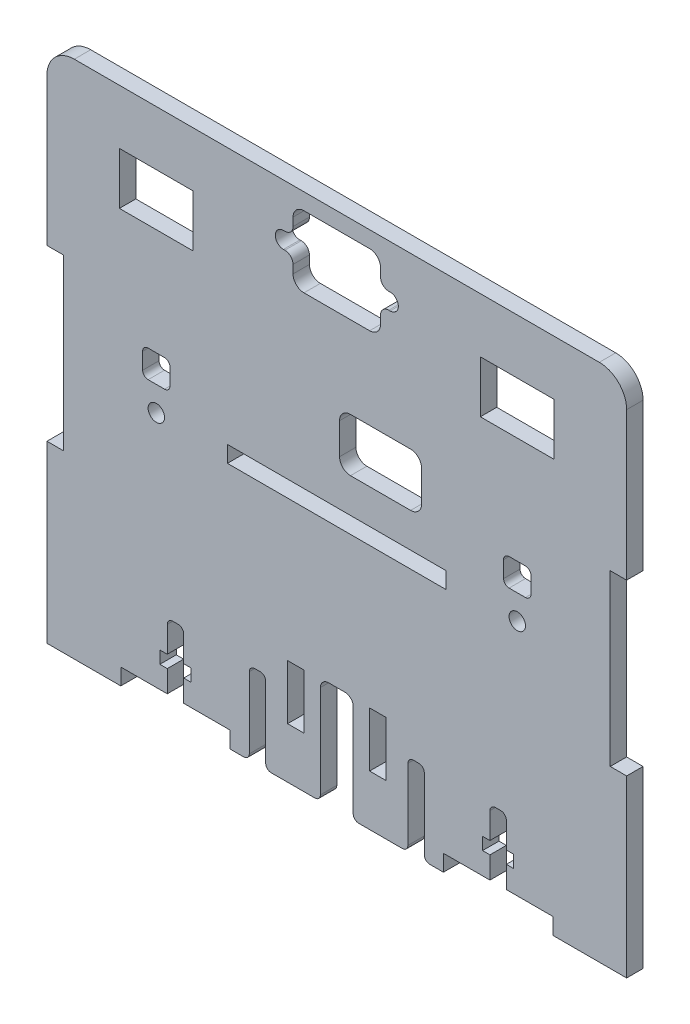
SolidWorks part; units mm, degrees
other "Marcação1"
sketch "Esboço7" plane through (-68, 31.5, 3) normal (-0.6758, 0.2828, 0.6807) x (0.7271, 0.1043, 0.6785)
sketch "Esboço8" plane through (-68, 31.5, 3) normal (-0.6758, 0.2828, 0.6807) x (0.7271, 0.1043, 0.6785)
sketch "Esboço9" plane through (-60.5, 31.5, 3) normal (-0.6758, 0.2828, 0.6807) x (0.7271, 0.1043, 0.6785)
sketch "Esboço12" plane through (-60.5, 31.5, 3) normal (-0.6758, 0.2828, 0.6807) x (0.7271, 0.1043, 0.6785)
sketch "Esboço14" plane through (-60.5, 31.5, 3) normal (-0.6758, 0.2828, 0.6807) x (0.7271, 0.1043, 0.6785)
sketch "Esboço15" plane through (-60.5, 36.25, 3) normal (-0.6758, 0.2828, 0.6807) x (0.7271, 0.1043, 0.6785)
sketch "Esboço18" plane through (-60.5, 33.25, 3) normal (-0.6758, 0.2828, 0.6807) x (0.7271, 0.1043, 0.6785)
sketch "Esboço20" plane through (-60.5, 29.8, 3) normal (-0.6758, 0.2828, 0.6807) x (0.7271, 0.1043, 0.6785)
sketch "Esboço22" plane through (-60.5, 29.8, 3) normal (-0.6758, 0.2828, 0.6807) x (0.7271, 0.1043, 0.6785)
material "Acrylic (Medium-high impact)"
ref_plane "Plano frontal" through (0, 0, 0) normal (0, 0, 1) x (1, 0, 0)
ref_plane "Plano superior" through (0, 0, 0) normal (0, 1, 0) x (1, 0, 0)
ref_plane "Plano direito" through (0, 0, 0) normal (1, 0, 0) x (0, 0, -1)
sketch "Esboço1" plane through (0, 0, 0) normal (0, 0, 1) x (1, 0, 0)
  line L1 (-50, -47.5) -> (50, -47.5)
  line L2 (-50, -47.5) -> (-50, 47.5)
  line L3 (-50, 47.5) -> (50, 47.5)
  line L4 (50, -47.5) -> (50, 47.5)
  line L5 (-50, -47.5) -> (50, 47.5) construction
  line L6 (-50, 47.5) -> (50, -47.5) construction
  point P0 (0, 0)
  dimension "D1" = 100
  dimension "D2" = 95
extrude "Ressalto-extrusão1" add sketch "Esboço1" along normal mid plane 3
sketch "Esboço3" plane through (0, 0, 1.5) normal (0, 0, 1) x (1, 0, 0)
  line L20 (50, 47.5) -> (-50, 47.5) construction
  line L21 (-53, 47.5) -> (-50, 47.5)
  line L22 (-53, 47.5) -> (-53, 15.5)
  line L23 (-53, 15.5) -> (-50, 15.5)
  line L24 (-50, 47.5) -> (-50, 15.5)
  line L25 (-50, 47.5) -> (-50, -47.5) construction
  line L26 (0, -1.65) -> (0, 1.65) construction
  line L27 (-50, -47.5) -> (-53, -47.5)
  line L28 (-50, -47.5) -> (-50, -15.5)
  line L29 (-50, -15.5) -> (-53, -15.5)
  line L30 (-53, -47.5) -> (-53, -15.5)
  line L31 (53, -47.5) -> (53, -15.5)
  line L32 (50, -15.5) -> (53, -15.5)
  line L33 (50, -47.5) -> (50, -15.5)
  line L34 (50, -47.5) -> (53, -47.5)
  line L35 (50, 47.5) -> (50, 15.5)
  line L36 (53, 15.5) -> (50, 15.5)
  line L37 (53, 47.5) -> (53, 15.5)
  line L38 (53, 47.5) -> (50, 47.5)
  dimension "D1" = 3
  dimension "D4" = 31
extrude "Ressalto-extrusão2" add sketch "Esboço3" against normal through all
sketch "Esboço2" plane through (0, 0, 1.5) normal (0, 0, 1) x (1, 0, 0)
  line L21 (-20, 0.5) -> (20, 0.5)
  line L22 (-20, 0.5) -> (-20, -2.5)
  line L23 (-20, -2.5) -> (20, -2.5)
  line L24 (20, 0.5) -> (20, -2.5)
  line L25 (-20, 0.5) -> (20, -2.5) construction
  line L26 (-20, -2.5) -> (20, 0.5) construction
  line L27 (0, -1.65) -> (0, 1.65) construction
  line L28 (-53, -47.5) -> (53, -47.5) construction
  circle A2 centre (-33, -1) radius 1.5
  circle A4 centre (33, -1) radius 1.5
  point P14 (0, -1)
  dimension "D4" = 13
  dimension "D8" = 3
  dimension "D3" = 45
  dimension "D6" = 3
  dimension "D13" = 40
extrude "Corte-extrusão1" cut sketch "Esboço2" against normal through all
sketch "Sketch4" plane through (0, 0, 1.5) normal (0, 0, 1) x (1, 0, 0)
  line L0 (-33, -2.5) -> (-33, 0.5) construction
  line L4 (0, -1.65) -> (0, 1.65) construction
  line L5 (-34.5, 8.5) -> (-31.5, 8.5)
  line L6 (-35.5, 7.5) -> (-35.5, 4.5)
  line L7 (-34.5, 3.5) -> (-31.5, 3.5)
  line L8 (-30.5, 7.5) -> (-30.5, 4.5)
  line L9 (30.5, 7.5) -> (30.5, 4.5)
  line L10 (34.5, 3.5) -> (31.5, 3.5)
  line L11 (35.5, 7.5) -> (35.5, 4.5)
  line L12 (34.5, 8.5) -> (31.5, 8.5)
  circle A1 centre (-33, -1) radius 1.5 construction
  arc A2 (-31.5, 8.5) -> (-30.5, 7.5) centre (-31.5, 7.5) cw
  arc A3 (-34.5, 8.5) -> (-35.5, 7.5) centre (-34.5, 7.5) ccw
  arc A4 (-35.5, 4.5) -> (-34.5, 3.5) centre (-34.5, 4.5) ccw
  arc A5 (-31.5, 3.5) -> (-30.5, 4.5) centre (-31.5, 4.5) ccw
  arc A6 (31.5, 3.5) -> (30.5, 4.5) centre (31.5, 4.5) cw
  arc A7 (35.5, 4.5) -> (34.5, 3.5) centre (34.5, 4.5) cw
  arc A8 (34.5, 8.5) -> (35.5, 7.5) centre (34.5, 7.5) cw
  arc A9 (31.5, 8.5) -> (30.5, 7.5) centre (31.5, 7.5) ccw
  point P10 (-33, 3.5)
  point P15 (-35.5, 8.5)
  point P18 (-35.5, 3.5)
  point P35 (35.5, 3.5)
  point P36 (35.5, 8.5)
  dimension "D1" = 5
  dimension "D2" = 5
  dimension "D4" = 1
  dimension "D3" = 3
extrude "Cut-Extrude3" cut sketch "Sketch4" against normal through all both and the other way through all
sketch "Sketch6" plane through (0, 0, 0) normal (0, 0, 1) x (1, 0, 0)
  line L0 (0, 44.5) -> (0, 31.5) construction
  line L2 (-6, 44.5) -> (6, 44.5)
  line L3 (-8, 42.5) -> (-8, 41)
  line L4 (-6, 31.5) -> (6, 31.5)
  line L5 (8, 42.5) -> (8, 41)
  line L6 (53, 47.5) -> (-53, 47.5) construction
  line L7 (-9.75, 39.5) -> (-9.5, 39.5)
  line L9 (-9.75, 36.5) -> (-9.5, 36.5)
  line L11 (-8, 35) -> (-8, 33.5)
  line L12 (9.75, 39.5) -> (9.5, 39.5)
  line L13 (9.75, 36.5) -> (9.5, 36.5)
  line L14 (8, 35) -> (8, 33.5)
  arc A0 (-9.75, 39.5) -> (-9.75, 36.5) centre (-9.75, 38) ccw
  arc A1 (9.75, 36.5) -> (9.75, 39.5) centre (9.75, 38) ccw
  arc A2 (-9.5, 36.5) -> (-8, 35) centre (-9.5, 35) cw
  arc A3 (-9.5, 39.5) -> (-8, 41) centre (-9.5, 41) ccw
  arc A4 (6, 31.5) -> (8, 33.5) centre (6, 33.5) ccw
  arc A5 (-8, 33.5) -> (-6, 31.5) centre (-6, 33.5) ccw
  arc A6 (6, 44.5) -> (8, 42.5) centre (6, 42.5) cw
  arc A7 (-6, 44.5) -> (-8, 42.5) centre (-6, 42.5) ccw
  arc A8 (9.5, 36.5) -> (8, 35) centre (9.5, 35) ccw
  arc A9 (9.5, 39.5) -> (8, 41) centre (9.5, 41) cw
  point P7 (0, 31.5)
  point P19 (-8, 36.5)
  point P26 (-8, 31.5)
  point P29 (8, 44.5)
  point P32 (-8, 44.5)
  point P37 (8, 36.5)
  dimension "D4" = 19.5
  dimension "D7" = 2
  dimension "D8" = 5
  dimension "D5" = 3
  dimension "D6" = 1.5
  dimension "D9" = 1.5
  dimension "D1" = 16
  dimension "D2" = 3
  dimension "D3" = 13
extrude "Cut-Extrude5" cut sketch "Sketch6" against normal through all both and the other way through all
sketch "Sketch7" plane through (0, 0, 0) normal (0, 0, 1) x (1, 0, 0)
  line L1 (-39.75, 37.5) -> (-26.25, 37.5)
  line L2 (-39.75, 37.5) -> (-39.75, 28)
  line L3 (-39.75, 28) -> (-26.25, 28)
  line L4 (-26.25, 37.5) -> (-26.25, 28)
  line L5 (0, -1.65) -> (0, 1.65) construction
  line L6 (-31.5, 8.5) -> (-34.5, 8.5) construction
  line L7 (-33, 3.5) -> (-33, 8.5) construction
  line L8 (-34.5, 3.5) -> (-31.5, 3.5) construction
  line L9 (26.25, 37.5) -> (26.25, 28)
  line L10 (39.75, 28) -> (26.25, 28)
  line L11 (39.75, 37.5) -> (39.75, 28)
  line L12 (39.75, 37.5) -> (26.25, 37.5)
  line L13 (53, 47.5) -> (-53, 47.5) construction
  point P13 (-33, 28)
  dimension "D1" = 13.5
  dimension "D2" = 9.5
  dimension "D3" = 10
extrude "Cut-Extrude6" cut sketch "Sketch7" against normal through all both and the other way through all
sketch "Sketch8" plane through (0, 0, 0) normal (0, 0, 1) x (1, 0, 0)
  line L0 (0, -1.65) -> (0, 1.65) construction
  line L1 (-9, -28.23) -> (-6, -28.23)
  line L2 (-9, -28.23) -> (-9, -38.23)
  line L3 (-9, -38.23) -> (-6, -38.23)
  line L4 (-6, -28.23) -> (-6, -38.23)
  line L5 (6, -28.23) -> (6, -38.23)
  line L6 (9, -38.23) -> (6, -38.23)
  line L7 (9, -28.23) -> (9, -38.23)
  line L8 (9, -28.23) -> (6, -28.23)
  line L9 (-53, -47.5) -> (53, -47.5) construction
  dimension "D1" = 3
  dimension "D2" = 10
  dimension "D3" = 12
  dimension "D4" = 9.27
extrude "Cut-Extrude7" cut sketch "Sketch8" against normal through all both and the other way through all
sketch "Sketch9" plane through (0, 0, 0) normal (0, 0, 1) x (1, 0, 0)
  line L1 (2.5, 16.5) -> (13.5, 16.5)
  line L2 (0.5, 14.5) -> (0.5, 8.8)
  line L3 (2.5, 6.8) -> (13.5, 6.8)
  line L4 (15.5, 14.5) -> (15.5, 8.8)
  line L5 (20, 0.5) -> (-20, 0.5) construction
  line L7 (8, 33.5) -> (8, 35) construction
  arc A0 (13.5, 16.5) -> (15.5, 14.5) centre (13.5, 14.5) cw
  arc A1 (13.5, 6.8) -> (15.5, 8.8) centre (13.5, 8.8) ccw
  arc A2 (0.5, 8.8) -> (2.5, 6.8) centre (2.5, 8.8) ccw
  arc A3 (2.5, 16.5) -> (0.5, 14.5) centre (2.5, 14.5) ccw
  point P8 (8, 16.5)
  point P13 (15.5, 16.5)
  point P20 (0.5, 16.5)
  dimension "D4" = 2
  dimension "D1" = 6.3
  dimension "D2" = 9.7
  dimension "D3" = 15
extrude "Cut-Extrude8" cut sketch "Sketch9" against normal through all both and the other way through all
sketch "Sketch11" plane through (0, 0, 0) normal (0, 0, 1) x (1, 0, 0)
  line L0 (0, -1.65) -> (0, 1.65) construction
  line L5 (-53, -47.5) -> (53, -47.5) construction
  line L6 (13, -33.5) -> (13, -47.5)
  line L7 (16, -47.5) -> (13, -47.5)
  line L12 (16, -33.5) -> (16, -47.5)
  line L13 (15, -32.5) -> (14, -32.5)
  line L15 (-1.5, -28) -> (1.5, -28)
  line L16 (-3, -29.5) -> (-3, -47.5)
  line L17 (-3, -47.5) -> (3, -47.5)
  line L18 (3, -29.5) -> (3, -47.5)
  line L19 (-6, -38.23) -> (-6, -28.23) construction
  line L20 (6, -28.23) -> (6, -38.23) construction
  line L22 (-15, -32.5) -> (-14, -32.5)
  line L23 (-16, -33.5) -> (-16, -47.5)
  line L24 (-16, -47.5) -> (-13, -47.5)
  line L25 (-13, -33.5) -> (-13, -47.5)
  line L29 (-9, -28.23) -> (-9, -38.23) construction
  arc A6 (1.5, -28) -> (3, -29.5) centre (1.5, -29.5) cw
  arc A7 (-1.5, -28) -> (-3, -29.5) centre (-1.5, -29.5) ccw
  arc A8 (-15, -32.5) -> (-16, -33.5) centre (-15, -33.5) ccw
  arc A9 (-14, -32.5) -> (-13, -33.5) centre (-14, -33.5) cw
  arc A10 (14, -32.5) -> (13, -33.5) centre (14, -33.5) ccw
  arc A11 (15, -32.5) -> (16, -33.5) centre (15, -33.5) cw
  point P18 (-14.5, -47.5)
  dimension "D3" = 3
  dimension "D7" = 15
  dimension "D9" = 6
  dimension "D4" = 1.5
  dimension "D8" = 1
  dimension "D1" = 19.5
  dimension "D2" = 3
  dimension "D5" = 3
  dimension "D6" = 5.5
extrude "Cut-Extrude10" cut sketch "Sketch11" against normal through all both and the other way through all
sketch "Sketch12" plane through (0, 0, 0) normal (0, 0, 1) x (1, 0, 0)
  line L0 (-53, -47.5) -> (-16, -47.5) construction
  line L1 (-39.5, -47.5) -> (-19.5, -47.5)
  line L2 (-39.5, -47.5) -> (-39.5, -44.5)
  line L3 (-39.5, -44.5) -> (-31, -44.5)
  line L4 (-19.5, -47.5) -> (-19.5, -44.5)
  line L5 (-50, 15.5) -> (-50, -15.5) construction
  line L11 (-28, -44.5) -> (-19.5, -44.5)
  line L13 (-31, -44.5) -> (-31, -40.5)
  line L14 (-30, -32.5) -> (-29, -32.5)
  line L15 (-28, -44.5) -> (-28, -40.5)
  line L16 (-28, -38.23) -> (-26.65, -38.23)
  line L17 (-32.35, -38.23) -> (-31, -38.23)
  line L18 (-32.35, -38.23) -> (-32.35, -40.5)
  line L19 (-32.35, -40.5) -> (-31, -40.5)
  line L20 (-26.65, -38.23) -> (-26.65, -40.5)
  line L21 (-31, -38.23) -> (-31, -33.5)
  line L22 (-28, -40.5) -> (-26.65, -40.5)
  line L23 (-28, -38.23) -> (-28, -33.5)
  line L24 (0, -1.65) -> (0, 1.65) construction
  line L25 (28, -38.23) -> (28, -33.5)
  line L26 (28, -40.5) -> (26.65, -40.5)
  line L27 (31, -38.23) -> (31, -33.5)
  line L28 (26.65, -38.23) -> (26.65, -40.5)
  line L29 (32.35, -40.5) -> (31, -40.5)
  line L30 (32.35, -38.23) -> (32.35, -40.5)
  line L31 (32.35, -38.23) -> (31, -38.23)
  line L32 (28, -38.23) -> (26.65, -38.23)
  line L33 (28, -44.5) -> (28, -40.5)
  line L34 (30, -32.5) -> (29, -32.5)
  line L35 (31, -44.5) -> (31, -40.5)
  line L36 (28, -44.5) -> (19.5, -44.5)
  line L37 (19.5, -47.5) -> (19.5, -44.5)
  line L38 (39.5, -44.5) -> (31, -44.5)
  line L39 (39.5, -47.5) -> (39.5, -44.5)
  line L40 (39.5, -47.5) -> (19.5, -47.5)
  arc A0 (-29, -32.5) -> (-28, -33.5) centre (-29, -33.5) cw
  arc A1 (-31, -33.5) -> (-30, -32.5) centre (-30, -33.5) cw
  arc A2 (31, -33.5) -> (30, -32.5) centre (30, -33.5) ccw
  arc A3 (29, -32.5) -> (28, -33.5) centre (29, -33.5) ccw
  point P19 (-29.5, -32.5)
  point P20 (-29.5, -47.5)
  point P23 (-28, -32.5)
  point P26 (-31, -32.5)
  point P51 (31, -32.5)
  point P52 (28, -32.5)
  dimension "D7" = 1
  dimension "D1" = 3
  dimension "D2" = 20
  dimension "D3" = 10.5
  dimension "D5" = 3
  dimension "D6" = 12
  dimension "D8" = 2.27
  dimension "D9" = 1.35
  dimension "D10" = 1.35
  dimension "D11" = 4
extrude "Cut-Extrude11" cut sketch "Sketch12" against normal through all both and the other way through all
fillet "Fillet1" radius 1 6 edges at (16, -47.5, 0) (13, -47.5, 0) (-13, -47.5, 0) (-16, -47.5, 0) (3, -47.5, 0) (-3, -47.5, 0)
fillet "Fillet2" radius 5 2 edges at (53, 47.5, 0) (-53, 47.5, 0)
